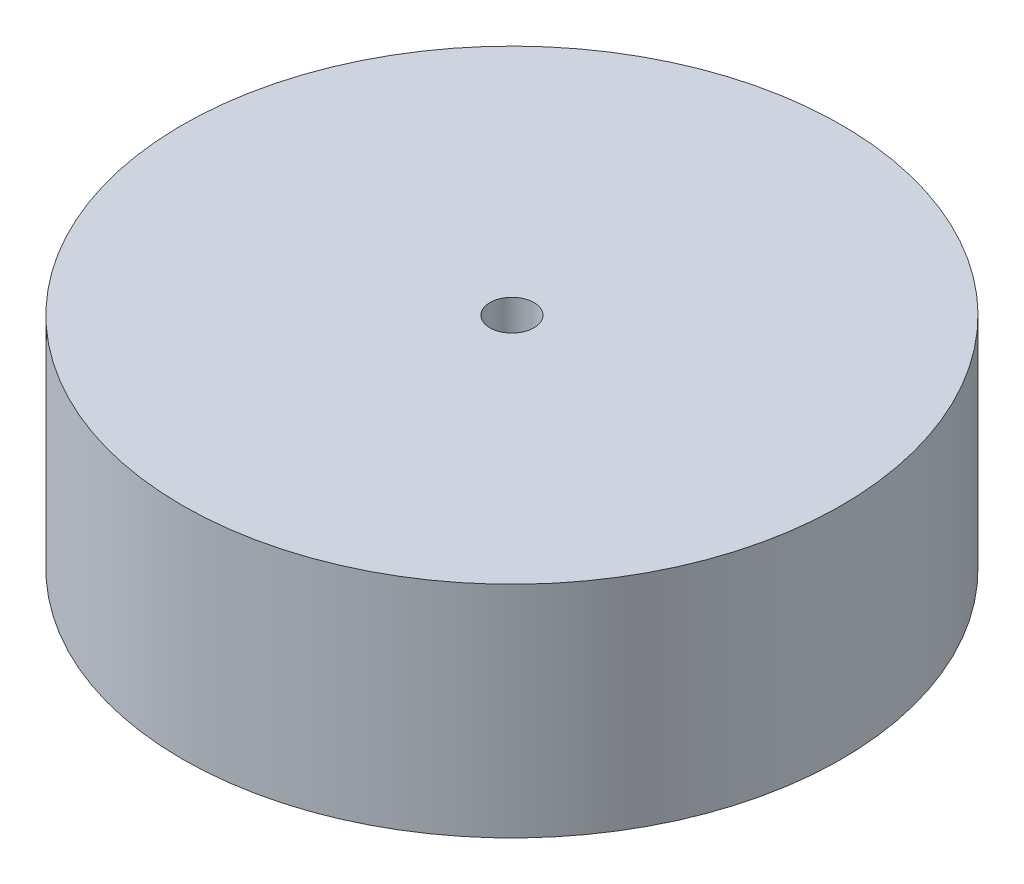
SolidWorks part; units mm, degrees
ref_plane "前基準面" through (0, 0, 0) normal (0, 0, 1) x (1, 0, 0)
ref_plane "上基準面" through (0, 0, 0) normal (0, 1, 0) x (1, 0, 0)
ref_plane "右基準面" through (0, 0, 0) normal (1, 0, 0) x (0, 0, -1)
sketch "草圖1" plane through (0, 0, 0) normal (0, 1, 0) x (1, 0, 0)
  circle A0 centre (0, 0) radius 15
  circle A1 centre (0, 0) radius 1
  dimension "D1" = 30
  dimension "D2" = 2
extrude "填料-伸長1" add sketch "草圖1" along normal blind 10
